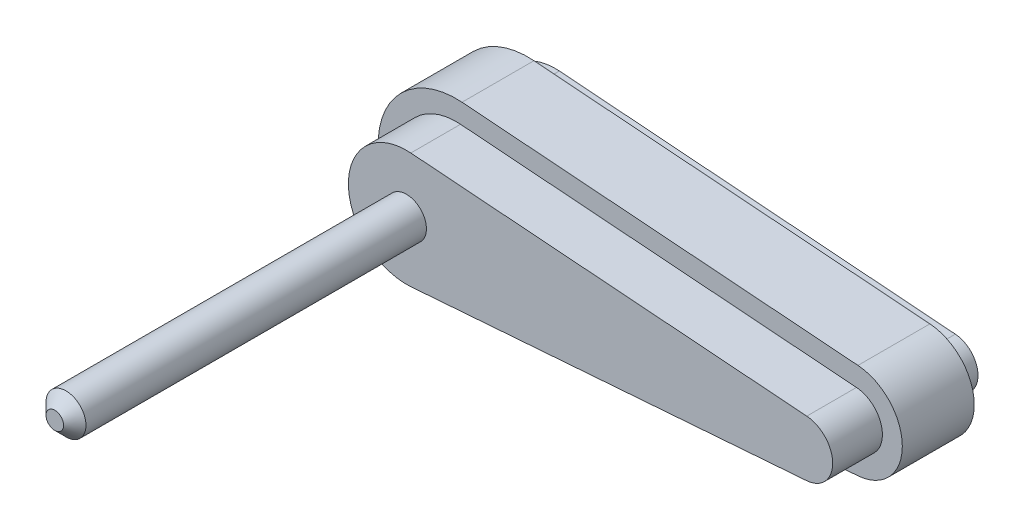
SolidWorks part; units mm, degrees
ref_plane "Front Plane" through (0, 0, 0) normal (0, 0, 1) x (1, 0, 0)
ref_plane "Top Plane" through (0, 0, 0) normal (0, 1, 0) x (1, 0, 0)
ref_plane "Right Plane" through (0, 0, 0) normal (1, 0, 0) x (0, 0, -1)
sketch "Sketch1" plane through (0, 0, 0) normal (0, 0, 1) x (1, 0, 0)
  line L0 (0.6954, 9.2003) -> (63.6137, 4.445)
  line L1 (0.6954, -9.2003) -> (63.6137, -4.445)
  line L2 (-9.2265, 0) -> (67.7354, 0) construction
  arc A0 (0.6954, 9.2003) -> (0.6954, -9.2003) centre (0, 0) ccw
  arc A1 (63.6137, 4.445) -> (63.6137, -4.445) centre (63.2778, 0) cw
  dimension "D1" = 18.4531
  dimension "D2" = 76.962
  dimension "D3" = 8.89
extrude "Boss-Extrude1" add sketch "Sketch1" against normal blind 23.6474
sketch "Sketch2" plane through (0, 0, -23.6474) normal (0, 0, -1) x (-1, 0, 0)
  line L0 (-0.6532, 8.6431) -> (-63.5716, 3.8878)
  line L1 (-63.5716, -3.8878) -> (-0.6532, -8.6431)
  line L2 (-0.6954, 9.2003) -> (-63.6137, 4.445)
  line L3 (-63.6137, -4.445) -> (-0.6954, -9.2003)
  line L4 (-0.6954, 9.2003) -> (-63.6137, 4.445)
  line L5 (-63.6137, -4.445) -> (-0.6954, -9.2003)
  arc A0 (-63.5716, 3.8878) -> (-63.5716, -3.8878) centre (-63.2778, 0) ccw
  arc A1 (-0.6532, -8.6431) -> (-0.6532, 8.6431) centre (0, 0) ccw
  arc A2 (-0.6954, -9.2003) -> (-0.6954, 9.2003) centre (0, 0) ccw
  arc A3 (-63.6137, 4.445) -> (-63.6137, -4.445) centre (-63.2778, 0) ccw
  arc A4 (-0.6954, -9.2003) -> (-0.6954, 9.2003) centre (0, 0) ccw
  arc A5 (-63.6137, 4.445) -> (-63.6137, -4.445) centre (-63.2778, 0) ccw
  dimension "D1" = 0
  dimension "D2" = 0.5588
extrude "Cut-Extrude1" cut sketch "Sketch2" against normal blind 15.748
sketch "Sketch3" plane through (0, 0, 0) normal (0, 0, 1) x (1, 0, 0)
  circle A0 centre (0, 0) radius 3.175
  dimension "D1" = 6.35
extrude "Boss-Extrude2" add sketch "Sketch3" along normal blind 55.88
sketch "Sketch4" plane through (0, 0, -7.8994) normal (0, 0, -1) x (-1, 0, 0)
  line L0 (-0.9337, 12.3536) -> (-63.852, 7.5983)
  line L1 (-63.852, -7.5983) -> (-0.9337, -12.3536)
  line L2 (-0.6532, 8.6431) -> (-63.5716, 3.8878)
  line L3 (-63.5716, -3.8878) -> (-0.6532, -8.6431)
  line L4 (-0.6532, 8.6431) -> (-63.5716, 3.8878)
  line L5 (-63.5716, -3.8878) -> (-0.6532, -8.6431)
  arc A0 (-63.852, 7.5983) -> (-63.852, -7.5983) centre (-63.2778, 0) ccw
  arc A1 (-0.9337, -12.3536) -> (-0.9337, 12.3536) centre (0, 0) ccw
  arc A2 (-0.6532, -8.6431) -> (-0.6532, 8.6431) centre (0, 0) ccw
  arc A3 (-63.5716, 3.8878) -> (-63.5716, -3.8878) centre (-63.2778, 0) ccw
  arc A4 (-0.6532, -8.6431) -> (-0.6532, 8.6431) centre (0, 0) ccw
  arc A5 (-63.5716, 3.8878) -> (-63.5716, -3.8878) centre (-63.2778, 0) ccw
  dimension "D1" = 0
  dimension "D2" = 3.7211
extrude "Boss-Extrude3" add sketch "Sketch4" along normal blind 11.43
chamfer "Chamfer1" distance 1.778 angle 45 1 edges at (3.175, 0, 55.88)
